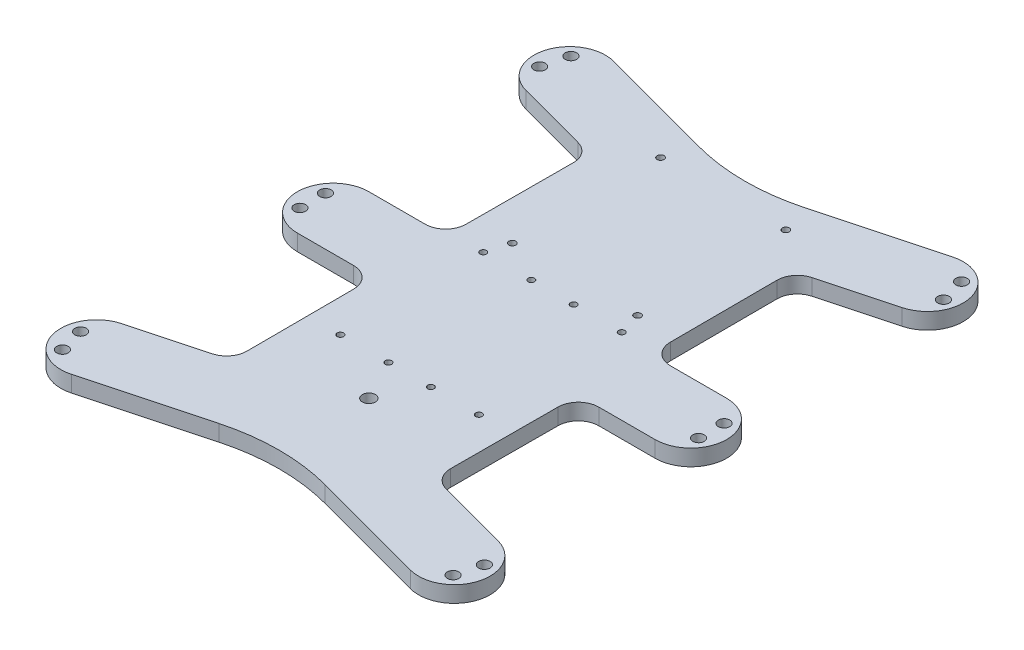
SolidWorks part; units mm, degrees
ref_plane "Front Plane" through (0, 0, 0) normal (0, 0, 1) x (1, 0, 0)
ref_plane "Top Plane" through (0, 0, 0) normal (0, 1, 0) x (1, 0, 0)
ref_plane "Right Plane" through (0, 0, 0) normal (1, 0, 0) x (0, 0, -1)
sketch "Sketch1" plane through (0, 0, 0) normal (0, 1, 0) x (1, 0, 0)
  line L0 (0, 32.1883) -> (0, -21.4181) construction
  line L1 (0, 0) -> (27.1703, 0) construction
  line L2 (-70, 14) -> (-40, 14)
  line L3 (-40, 14) -> (-39.8161, 70)
  line L4 (-39.8161, 70) -> (-73.6235, 79.0587)
  line L5 (-66.3765, 106.1046) -> (0, 88.3191)
  line L10 (-66.3765, 106.1046) -> (-73.6235, 79.0587) construction
  line L12 (-70, 14) -> (-70, -14) construction
  line L14 (-66.3765, -106.1046) -> (0, -88.3191)
  line L15 (-39.8161, -70) -> (-73.6235, -79.0587)
  line L16 (-40, -14) -> (-39.8161, -70)
  line L17 (-70, -14) -> (-40, -14)
  line L18 (66.3765, -106.1046) -> (0, -88.3191)
  line L19 (66.3765, 106.1046) -> (0, 88.3191)
  line L20 (70, 14) -> (70, -14) construction
  line L21 (66.3765, 106.1046) -> (73.6235, 79.0587) construction
  line L22 (70, -14) -> (40, -14)
  line L23 (40, -14) -> (39.8161, -70)
  line L24 (39.8161, -70) -> (73.6235, -79.0587)
  line L25 (39.8161, 70) -> (73.6235, 79.0587)
  line L26 (40, 14) -> (39.8161, 70)
  line L27 (70, 14) -> (40, 14)
  arc A0 (-70, 14) -> (-70, -14) centre (-70, 0) ccw
  arc A1 (-66.3765, 106.1046) -> (-73.6235, 79.0587) centre (-70, 92.5816) ccw
  arc A11 (-66.3765, -106.1046) -> (-73.6235, -79.0587) centre (-70, -92.5816) cw
  arc A18 (66.3765, -106.1046) -> (73.6235, -79.0587) centre (70, -92.5816) ccw
  arc A22 (66.3765, 106.1046) -> (73.6235, 79.0587) centre (70, 92.5816) cw
  arc A23 (70, 14) -> (70, -14) centre (70, 0) cw
  point P118 (-83.523, 96.2051)
  dimension "D2" = 14
  dimension "D3" = 70
  dimension "D1" = 75
  dimension "D5" = 30
  dimension "D6" = 35
  dimension "D7" = 56
extrude "Boss-Extrude1" add sketch "Sketch1" along normal blind 6.35
fillet "Fillet1" radius 80 2 edges at (0, 3.175, -88.3191) (0, 3.175, 88.3191)
fillet "Fillet2" radius 8 8 edges at (39.8161, 3.175, 70) (40, 3.175, 14) (40, 3.175, -14) (39.8161, 3.175, -70) (-39.8161, 3.175, -70) (-40, 3.175, -14) (-40, 3.175, 14) (-39.8161, 3.175, 70)
sketch "Sketch2" plane through (0, 6.35, 0) normal (0, 1, 0) x (1, 0, 0)
  circle A0 centre (-24.5, 24.6411) radius 1.35 construction
  circle A1 centre (24.5, 24.6411) radius 1.35 construction
  circle A2 centre (24.5, 82.6411) radius 1.35 construction
  circle A3 centre (-24.5, 82.6411) radius 1.35 construction
  circle A4 centre (-24.5, 24.6411) radius 1.35
  circle A5 centre (24.5, 24.6411) radius 1.35
  circle A6 centre (24.5, 82.6411) radius 1.35
  circle A7 centre (-24.5, 82.6411) radius 1.35
extrude "Cut-Extrude1" cut sketch "Sketch2" against normal through all
sketch "Sketch3" plane through (0, 6.35, 0) normal (0, 1, 0) x (1, 0, 0)
  circle A0 centre (-8.3, -40.0589) radius 1.25 construction
  circle A1 centre (-27.1, -40.0589) radius 1.25 construction
  circle A2 centre (-27.1, 15.8411) radius 1.25 construction
  circle A3 centre (-8.3, 15.8411) radius 1.25 construction
  circle A4 centre (8.3, 15.8411) radius 1.25 construction
  circle A5 centre (27.1, 15.8411) radius 1.25 construction
  circle A6 centre (8.3, -40.0589) radius 1.25 construction
  circle A7 centre (27.1, -40.0589) radius 1.25 construction
  circle A8 centre (-8.3, -40.0589) radius 1.25
  circle A9 centre (-27.1, -40.0589) radius 1.25
  circle A10 centre (-27.1, 15.8411) radius 1.25
  circle A11 centre (-8.3, 15.8411) radius 1.25
  circle A12 centre (8.3, 15.8411) radius 1.25
  circle A13 centre (27.1, 15.8411) radius 1.25
  circle A14 centre (8.3, -40.0589) radius 1.25
  circle A15 centre (27.1, -40.0589) radius 1.25
extrude "Cut-Extrude2" cut sketch "Sketch3" against normal through all
sketch "Sketch5" plane through (0, 6.35, 0) normal (0, 1, 0) x (1, 0, 0)
  line L0 (-39.862, -56.0189) -> (39.862, -56.0189) construction
  line L1 (-39.9738, -21.9737) -> (-39.8363, -63.8405) construction
  line L2 (39.8363, -63.8405) -> (39.9738, -21.9737) construction
  line L3 (-27.1, -43.3589) -> (-8.3, -43.3589) construction
  circle A0 centre (0, -56.0189) radius 2.55
  point P6 (0, -56.0189)
  dimension "D2" = 5.1
  dimension "D1" = 12.66
extrude "Cut-Extrude3" cut sketch "Sketch5" against normal through all
sketch "Sketch7" plane through (0, 6.35, 0) normal (0, 1, 0) x (1, 0, 0)
  circle A0 centre (-76.4333, -99.4818) radius 2.25 construction
  circle A1 centre (-79.0215, -89.8226) radius 2.25 construction
  circle A2 centre (-78, -5) radius 2.25 construction
  circle A3 centre (-78, 5) radius 2.25 construction
  circle A4 centre (-79.0215, 89.8226) radius 2.25 construction
  circle A5 centre (-76.4333, 99.4818) radius 2.25 construction
  circle A6 centre (79.0215, 89.8226) radius 2.25 construction
  circle A7 centre (76.4333, 99.4818) radius 2.25 construction
  circle A8 centre (78, -5) radius 2.25 construction
  circle A9 centre (78, 5) radius 2.25 construction
  circle A10 centre (79.0215, -89.8226) radius 2.25 construction
  circle A11 centre (76.4333, -99.4818) radius 2.25 construction
  circle A12 centre (-76.4333, -99.4818) radius 2.25
  circle A13 centre (-79.0215, -89.8226) radius 2.25
  circle A14 centre (-78, -5) radius 2.25
  circle A15 centre (-78, 5) radius 2.25
  circle A16 centre (-79.0215, 89.8226) radius 2.25
  circle A17 centre (-76.4333, 99.4818) radius 2.25
  circle A18 centre (79.0215, 89.8226) radius 2.25
  circle A19 centre (76.4333, 99.4818) radius 2.25
  circle A20 centre (78, -5) radius 2.25
  circle A21 centre (78, 5) radius 2.25
  circle A22 centre (79.0215, -89.8226) radius 2.25
  circle A23 centre (76.4333, -99.4818) radius 2.25
extrude "Cut-Extrude4" cut sketch "Sketch7" against normal blind 10
